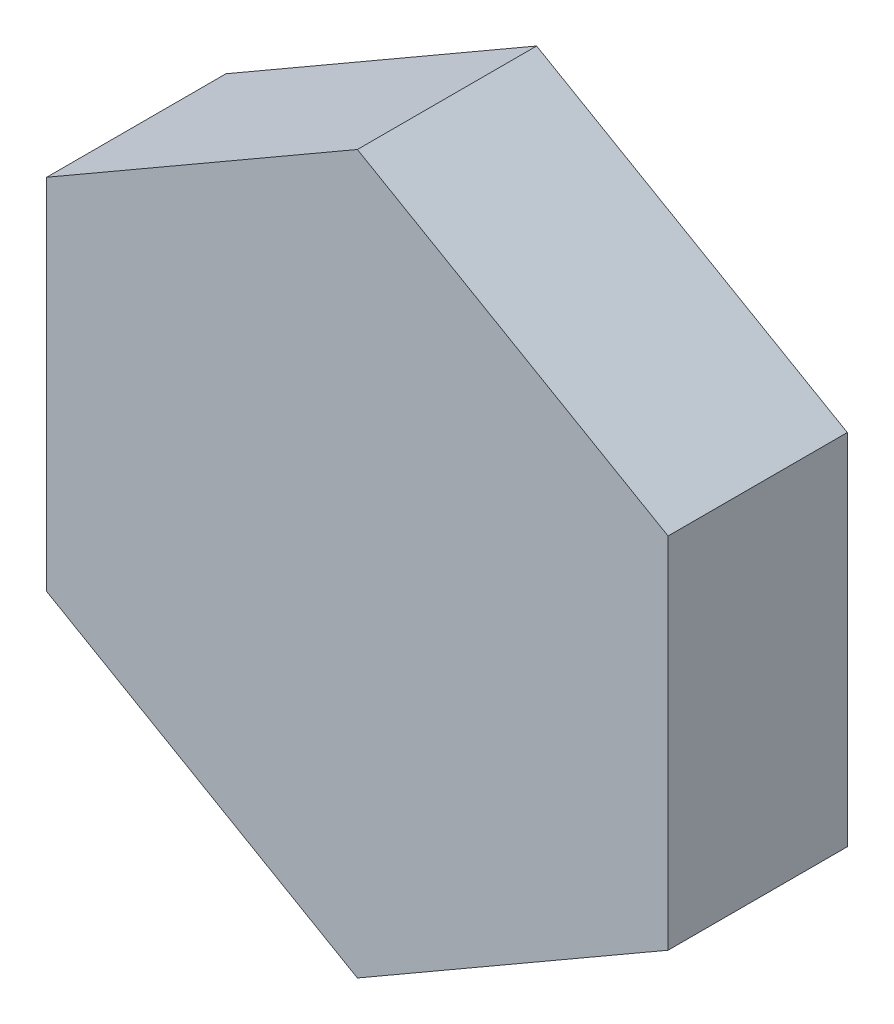
SolidWorks part; units mm, degrees
ref_plane "Front Plane" through (0, 0, 0) normal (0, 0, 1) x (1, 0, 0)
ref_plane "Top Plane" through (0, 0, 0) normal (0, 1, 0) x (1, 0, 0)
ref_plane "Right Plane" through (0, 0, 0) normal (1, 0, 0) x (0, 0, -1)
sketch "Sketch4" plane through (0, 0, 0) normal (0, 0, 1) x (1, 0, 0)
  line L1 (0, -270.1999) -> (234, -135.1)
  line L2 (234, -135.1) -> (234, 135.1)
  line L3 (234, 135.1) -> (0, 270.1999)
  line L4 (0, 270.1999) -> (-234, 135.1)
  line L5 (-234, 135.1) -> (-234, -135.1)
  line L6 (-234, -135.1) -> (0, -270.1999)
  circle A0 centre (0, 0) radius 234 construction
  dimension "D1" = 468
extrude "Boss-Extrude1" add sketch "Sketch4" along normal blind 135
sketch "Sketch5" plane through (0, 0, 135) normal (0, 0, 1) x (1, 0, 0)
  circle A0 centre (160, 0) radius 35
  dimension "D2" = 70
  dimension "D1" = 160
